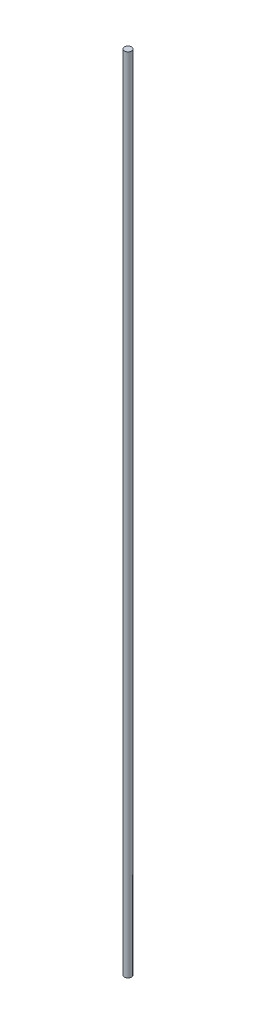
SolidWorks part; units mm, degrees
material "1060 Alloy"
ref_plane "Front Plane" through (0, 0, 0) normal (0, 0, 1) x (1, 0, 0)
ref_plane "Top Plane" through (0, 0, 0) normal (0, 1, 0) x (1, 0, 0)
ref_plane "Right Plane" through (0, 0, 0) normal (1, 0, 0) x (0, 0, -1)
sketch "Sketch1" plane through (0, 0, 0) normal (0, 1, 0) x (1, 0, 0)
  circle A0 centre (0, 0) radius 4.0005
  dimension "D1" = 8.001
extrude "Boss-Extrude1" add sketch "Sketch1" along normal blind 889
